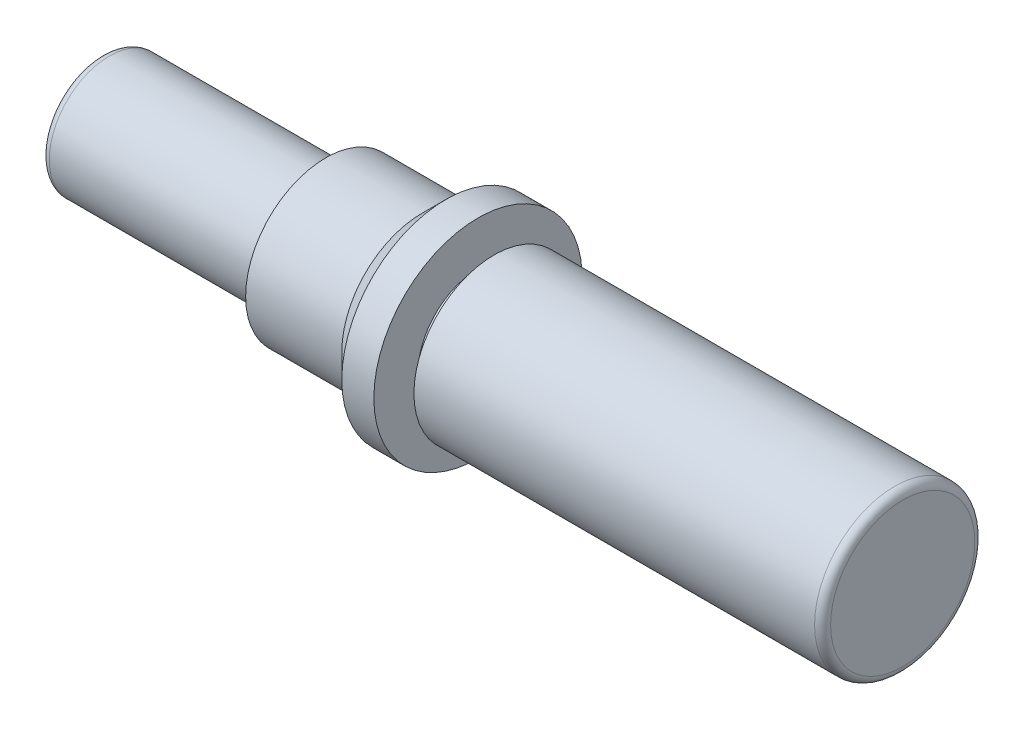
SolidWorks part; units mm, degrees
ref_plane "Front Plane" through (0, 0, 0) normal (0, 0, 1) x (1, 0, 0)
ref_plane "Top Plane" through (0, 0, 0) normal (0, 1, 0) x (1, 0, 0)
ref_plane "Right Plane" through (0, 0, 0) normal (1, 0, 0) x (0, 0, -1)
sketch "Sketch1" plane through (0, 0, 0) normal (0, 0, 1) x (1, 0, 0)
  line L0 (-61.6998, 9.8978) -> (-61.6998, 17.3978)
  line L1 (-61.6998, 17.3978) -> (-33.6998, 17.3978)
  line L2 (-33.6998, 17.3978) -> (-33.6998, 19.8978)
  line L3 (-33.6998, 19.8978) -> (-21.6998, 19.8978)
  line L4 (-21.6998, 19.8978) -> (-18.6998, 22.8978)
  line L5 (-18.6998, 22.8978) -> (-14.6998, 22.8978)
  line L6 (-14.6998, 22.8978) -> (-14.6998, 17.3978)
  line L7 (-14.6998, 17.3978) -> (-12.6998, 17.3978)
  line L8 (-12.6998, 17.3978) -> (-12.6998, 19.8978)
  line L9 (-12.6998, 19.8978) -> (38.3002, 19.8978)
  line L10 (38.3002, 19.8978) -> (38.3002, 9.8978)
  line L11 (-61.6998, 9.8978) -> (41.8177, 9.8978) construction
  line L12 (-61.6998, 9.8978) -> (38.3002, 9.8978)
  point P10 (0, 0)
  point P14 (0, 0)
  dimension "D1" = 7.5
  dimension "D2" = 28
  dimension "D3" = 10
  dimension "D4" = 135
  dimension "D5" = 13
  dimension "D6" = 7
  dimension "D7" = 2
  dimension "D8" = 10
  dimension "D9" = 53
  dimension "D10" = 12
  dimension "D11" = 7.5
revolve "Revolve1" add sketch "Sketch1" angle 360 about L11
fillet "Fillet1" radius 1 2 edges at (38.3002, 9.8978, 10) (-61.6998, 9.8978, 7.5)
